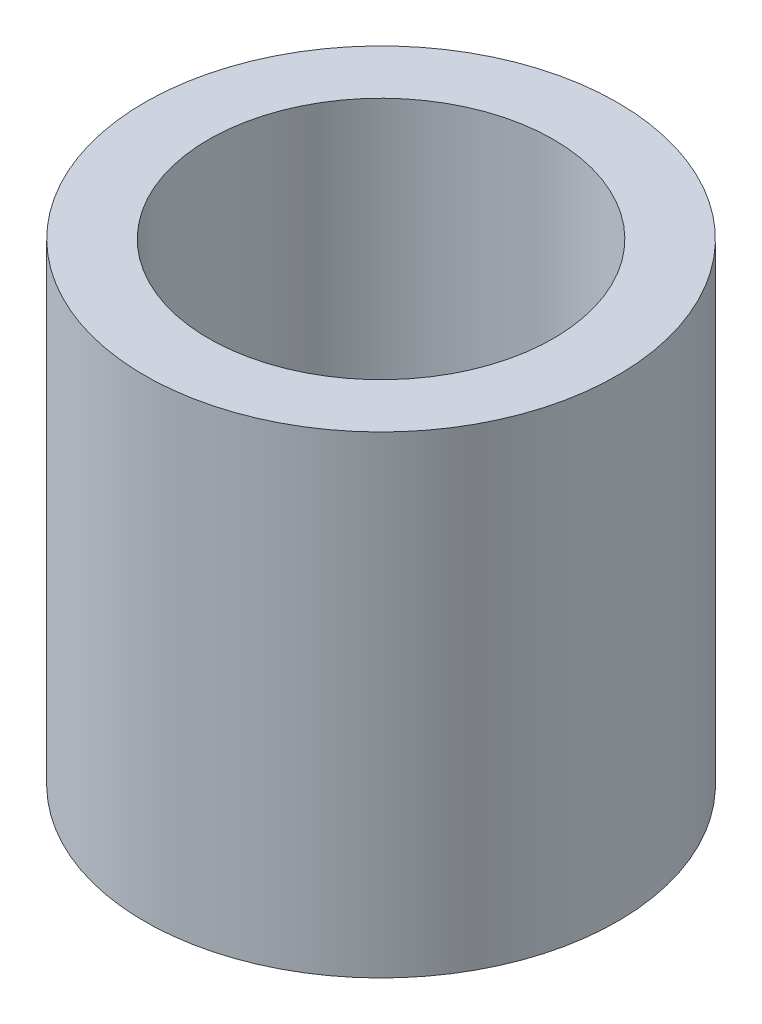
SolidWorks part; units mm, degrees
ref_plane "Front Plane" through (0, 0, 0) normal (0, 0, 1) x (1, 0, 0)
ref_plane "Top Plane" through (0, 0, 0) normal (0, 1, 0) x (1, 0, 0)
ref_plane "Right Plane" through (0, 0, 0) normal (1, 0, 0) x (0, 0, -1)
sketch "Sketch1" plane through (0, 0, 0) normal (0, 0, 1) x (1, 0, 0)
  line L0 (0, 0) -> (0, 3.3156) construction
  line L1 (1.2192, 0) -> (-1.2192, 0) construction
  line L2 (1.2192, 0) -> (0.889, 0)
  line L3 (1.2192, 0) -> (1.2192, 2.4384)
  line L4 (1.2192, 2.4384) -> (0.889, 2.4384)
  line L5 (0.889, 0) -> (0.889, 2.4384)
  line L6 (1.2192, 0) -> (0.889, 2.4384) construction
  line L7 (1.2192, 2.4384) -> (0.889, 0) construction
  point P7 (1.0541, 1.2192)
  dimension "D1" = 2.4384
  dimension "D2" = 1.778
revolve "Revolve1" add sketch "Sketch1" angle 360 about L0
